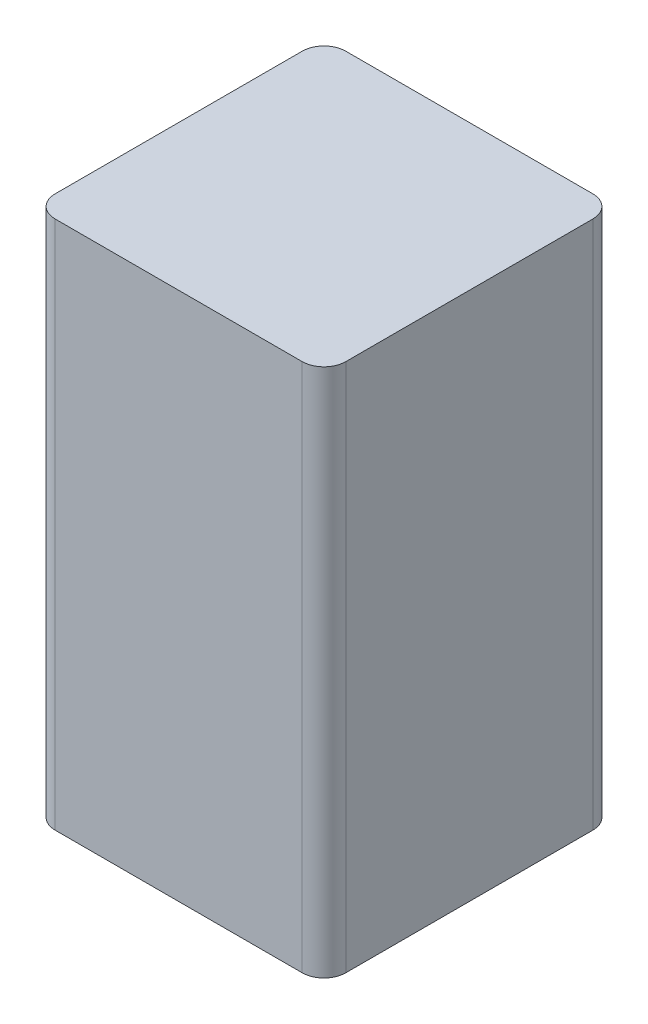
SolidWorks part; units mm, degrees
ref_plane "前视基准面" through (0, 0, 0) normal (0, 0, 1) x (1, 0, 0)
ref_plane "上视基准面" through (0, 0, 0) normal (0, 1, 0) x (1, 0, 0)
ref_plane "右视基准面" through (0, 0, 0) normal (1, 0, 0) x (0, 0, -1)
other "Configuration Table"
sketch "草图1" plane through (0, 0, 0) normal (0, 0, 1) x (1, 0, 0)
  line L0 (0, 0) -> (40, 0)
  line L1 (40, 0) -> (40, 72.85)
  line L2 (40, 72.85) -> (0, 72.85)
  line L3 (0, 72.85) -> (0, 0)
  dimension "width" = 40
  dimension "height" = 72.85
extrude "BlockExtrude" add sketch "草图1" along normal blind 40
fillet "Fillet" radius 3 4 edges at (0, 36.425, 0) (40, 36.425, 0) (0, 36.425, 40) (40, 36.425, 40)
sketch "草图2" plane through (0, 0, 0) normal (0, -1, 0) x (1, 0, 0)
  circle A0 centre (20, 20) radius 4.15
  dimension "diameter" = 8.3
  dimension "x" = 20
  dimension "y" = 20
extrude "Motor_shaft_socket" cut sketch "草图2" against normal blind 26
